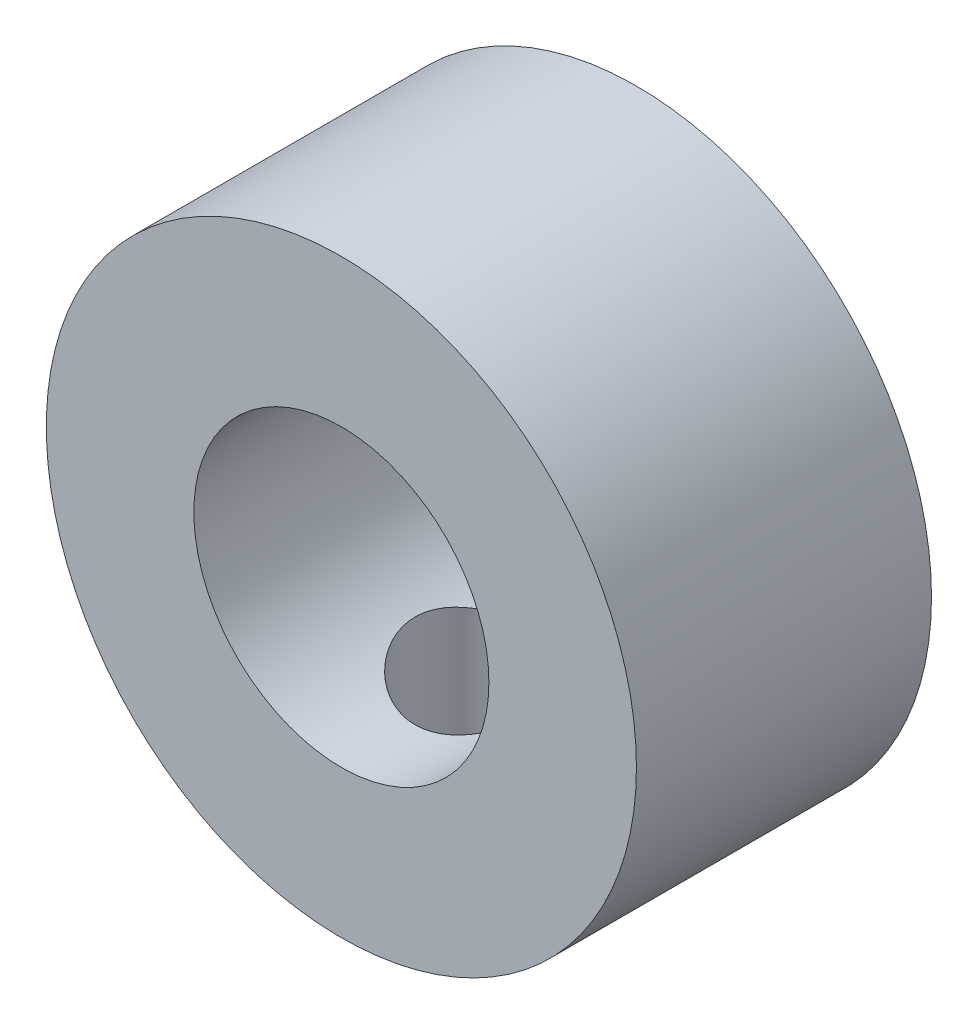
SolidWorks part; units mm, degrees
ref_plane "Front Plane" through (0, 0, 0) normal (0, 0, 1) x (1, 0, 0)
ref_plane "Top Plane" through (0, 0, 0) normal (0, 1, 0) x (1, 0, 0)
ref_plane "Right Plane" through (0, 0, 0) normal (1, 0, 0) x (0, 0, -1)
sketch "Sketch1" plane through (0, 0, 0) normal (0, 0, 1) x (1, 0, 0)
  circle A0 centre (0, 0) radius 2.5
  circle A1 centre (0, 0) radius 5
  dimension "D1" = 5
  dimension "D2" = 10
extrude "Boss-Extrude1" add sketch "Sketch1" along normal blind 5
sketch "Sketch2" plane through (0, 0, 0) normal (0, 1, 0) x (1, 0, 0)
  line L0 (2.5, 0) -> (-2.5, 0) construction
  circle A0 centre (0, -2.5) radius 1.25
  dimension "D2" = 2.5
  dimension "D1" = 2.5
extrude "Cut-Extrude1" cut sketch "Sketch2" against normal through all
sketch "Sketch3" plane through (0, 0, 5) normal (0, 0, 1) x (1, 0, 0)
  line L0 (0, 0) -> (6.4999, 0)
